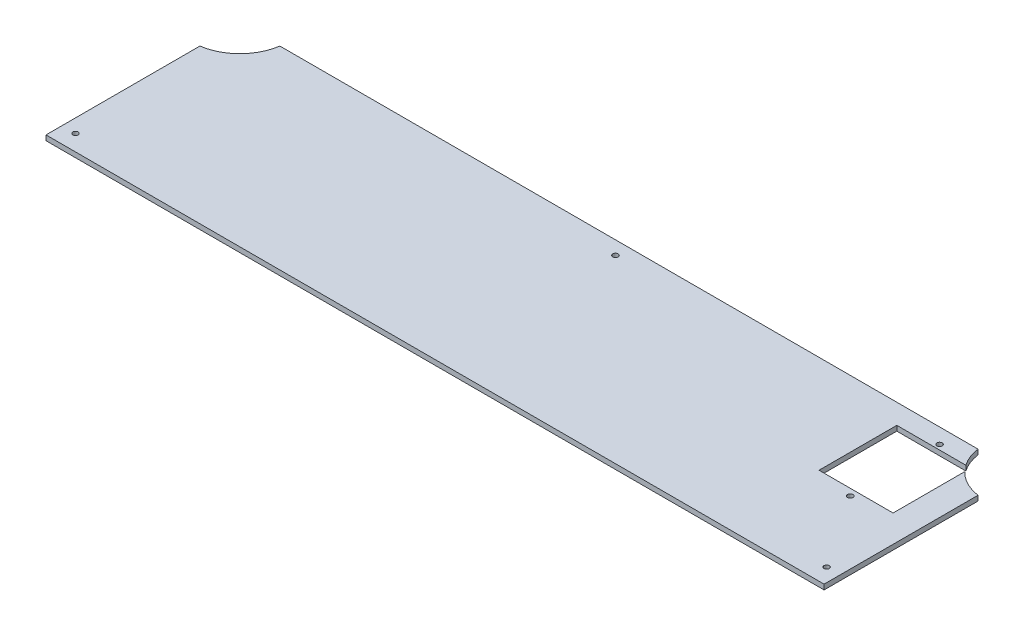
SolidWorks part; units mm, degrees
ref_plane "Alzado" through (0, 0, 0) normal (0, 0, 1) x (1, 0, 0)
ref_plane "Planta" through (0, 0, 0) normal (0, 1, 0) x (1, 0, 0)
ref_plane "Vista lateral" through (0, 0, 0) normal (1, 0, 0) x (0, 0, -1)
sketch "Croquis1" plane through (0, 0, 0) normal (0, 1, 0) x (1, 0, 0)
  line L26 (230.8475, -52.6811) -> (230.8475, 34.3508)
  line L31 (207.1347, 58.0636) -> (-206.9396, 58.0636)
  line L32 (-230.6525, 34.3508) -> (-230.6525, -52.9364)
  line L33 (230.8475, -52.6811) -> (230.8475, -56.9364)
  line L34 (230.8475, -56.9364) -> (-230.6525, -56.9364)
  line L35 (-230.6525, -56.9364) -> (-230.6525, -52.9364)
  line L36 (206.2618, 35.4778) -> (180.4333, 9.6494) construction
  line L37 (170.8475, 0.0636) -> (214.7721, 0.0636)
  line L38 (170.8475, 0.0636) -> (170.8475, 46.193)
  line L39 (170.8475, 46.193) -> (211.7797, 46.193)
  line L40 (214.7721, 0.0636) -> (214.7721, 42.545)
  line L41 (170.8475, 0.0636) -> (206.2618, 35.4778) construction
  line L42 (170.8475, 46.193) -> (214.7721, 0.0636) construction
  arc A24 (207.1347, 58.0636) -> (211.7797, 46.193) centre (234.8475, 62.0636) ccw
  arc A25 (214.7721, 42.545) -> (230.8475, 34.3508) centre (234.8475, 62.0636) ccw
  circle A26 centre (193.3475, -3.9364) radius 1.6
  circle A27 centre (193.3475, 49.0636) radius 1.6
  circle A28 centre (222.8475, -47.4364) radius 1.55
  circle A29 centre (0.0975, 50.0636) radius 1.6
  circle A30 centre (-222.6525, -47.4364) radius 1.55
  arc A31 (-230.6525, 34.3508) -> (-206.9396, 58.0636) centre (-234.6525, 62.0636) ccw
  point P8 (193.3475, 22.5636)
  dimension "D1" = 28
  dimension "D2" = 28
extrude "Saliente-Extruir1" add sketch "Croquis1" along normal blind 3
